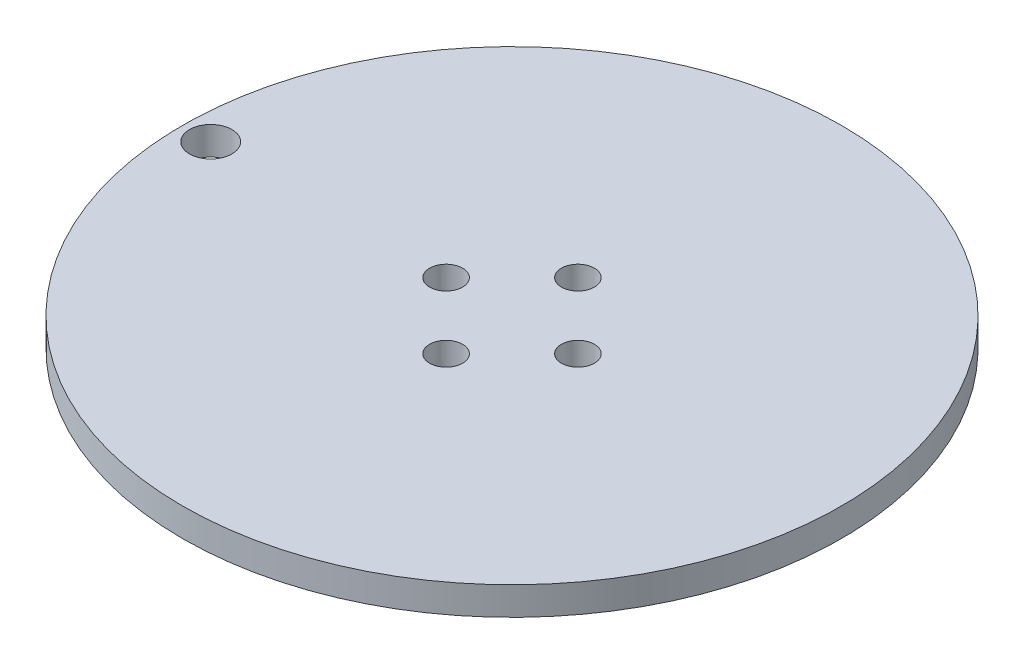
SolidWorks part; units mm, degrees
ref_plane "前视基准面" through (0, 0, 0) normal (0, 0, 1) x (1, 0, 0)
ref_plane "上视基准面" through (0, 0, 0) normal (0, 1, 0) x (1, 0, 0)
ref_plane "右视基准面" through (0, 0, 0) normal (1, 0, 0) x (0, 0, -1)
sketch "草图1" plane through (0, 0, 0) normal (0, 1, 0) x (1, 0, 0)
  line L0 (0, 0) -> (-7, 0) construction
  line L1 (0, 0) -> (-32, 0) construction
  circle A0 centre (0, 0) radius 35
  circle A1 centre (-7, 0) radius 1.75
  circle A2 centre (0, 7) radius 1.75
  circle A3 centre (7, 0) radius 1.75
  circle A4 centre (0, -7) radius 1.75
  circle A5 centre (-32, 0) radius 2.25
  point P14 (0, 0)
  dimension "D1" = 70
  dimension "D2" = 3.5
  dimension "D5" = 4.5
  dimension "D4" = 14
  dimension "D6" = 32
  dimension "D3" = 4
extrude "凸台-拉伸1" add sketch "草图1" along normal blind 3
